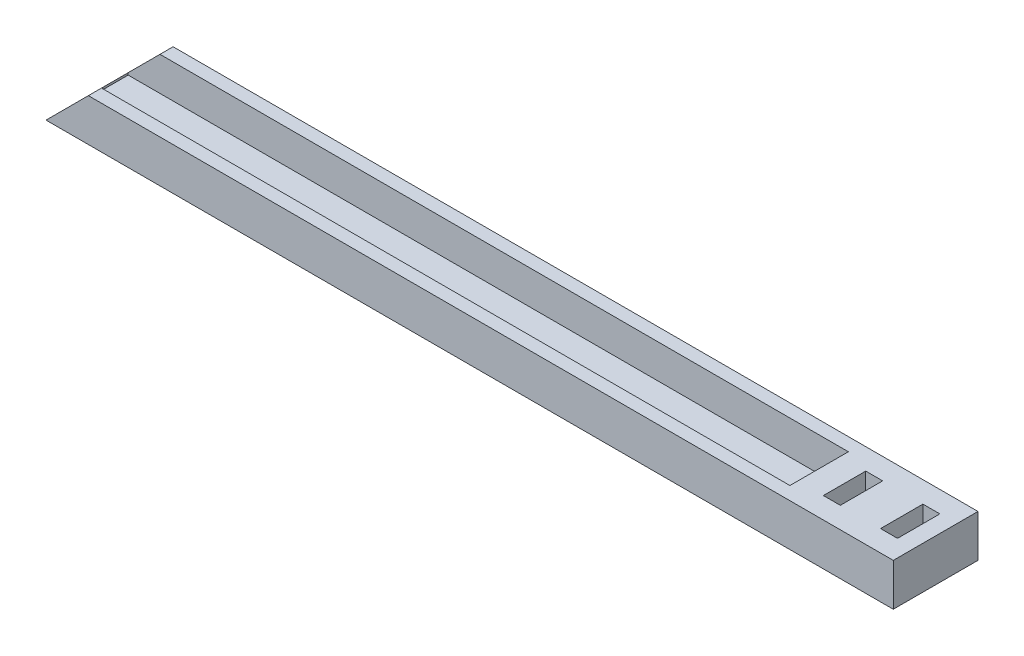
SolidWorks part; units mm, degrees
material "Copper"
ref_plane "Front Plane" through (0, 0, 0) normal (0, 0, 1) x (1, 0, 0)
ref_plane "Top Plane" through (0, 0, 0) normal (0, 1, 0) x (1, 0, 0)
ref_plane "Right Plane" through (0, 0, 0) normal (1, 0, 0) x (0, 0, -1)
sketch "Sketch1" plane through (0, 0, 0) normal (0, 1, 0) x (1, 0, 0)
  line L1 (0, 0) -> (254, 0)
  line L2 (0, 0) -> (0, 25.4)
  line L3 (0, 25.4) -> (254, 25.4)
  line L4 (254, 0) -> (254, 25.4)
  dimension "D1" = 254
  dimension "D2" = 25.4
extrude "Base Extrude" add sketch "Sketch1" along normal blind 12.7
sketch "Sketch3" plane through (0, 12.7, 0) normal (0, 1, 0) x (1, 0, 0)
  line L1 (3.175, 21.463) -> (219.075, 21.463)
  line L2 (3.175, 21.463) -> (3.175, 3.937)
  line L3 (3.175, 3.937) -> (219.075, 3.937)
  line L4 (219.075, 21.463) -> (219.075, 3.937)
  line L5 (0, 25.4) -> (0, 0) construction
  line L6 (3.175, 12.7) -> (219.075, 12.7) construction
  line L7 (254, 12.7) -> (0, 12.7) construction
  line L8 (254, 0) -> (254, 25.4) construction
  dimension "D1" = 17.526
  dimension "D3" = 3.175
  dimension "D4" = 215.9
extrude "Piece Cut" cut sketch "Sketch3" against normal blind 10.16
sketch "Sketch4" plane through (0, 0, -25.4) normal (0, 0, -1) x (-1, 0, 0)
  line L0 (0, 0) -> (-12.7, 12.7)
  line L1 (-254, 12.7) -> (0, 12.7) construction
  line L2 (0, 0) -> (0, 12.7)
  line L3 (0, 12.7) -> (-12.7, 12.7)
  dimension "D1" = 45
extrude "Corner Cut" cut sketch "Sketch4" against normal through all
sketch "Sketch6" plane through (0, 12.7, 0) normal (0, 1, 0) x (1, 0, 0)
  line L0 (226.695, 19.05) -> (231.775, 19.05)
  line L1 (243.84, 19.05) -> (248.92, 19.05)
  line L2 (243.84, 19.05) -> (243.84, 6.35)
  line L3 (243.84, 6.35) -> (248.92, 6.35)
  line L4 (248.92, 19.05) -> (248.92, 6.35)
  line L5 (254, 0) -> (254, 25.4) construction
  line L6 (254, 12.7) -> (219.075, 12.7) construction
  line L7 (219.075, 3.937) -> (219.075, 21.463) construction
  line L8 (243.84, 12.7) -> (248.92, 12.7) construction
  line L9 (226.695, 19.05) -> (226.695, 6.35)
  line L10 (226.695, 6.35) -> (231.775, 6.35)
  line L11 (231.775, 19.05) -> (231.775, 6.35)
  line L12 (226.695, 12.7) -> (231.775, 12.7) construction
  point P4 (246.38, 6.35)
  dimension "D1" = 5.08
  dimension "D2" = 12.7
  dimension "D3" = 5.08
  dimension "D4" = 5.08
  dimension "D5" = 12.7
  dimension "D6" = 22.225
extrude "Peg Cut" cut sketch "Sketch6" against normal blind 10.16
